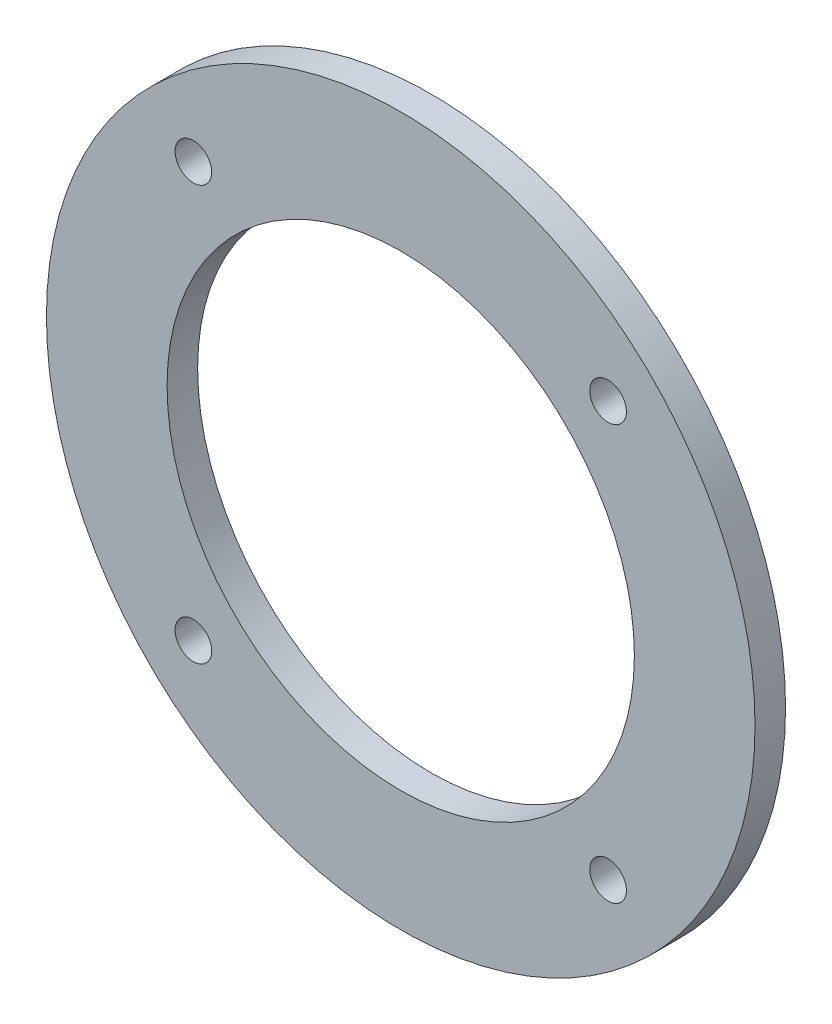
SolidWorks part; units mm, degrees
ref_plane "Front Plane" through (0, 0, 0) normal (0, 0, 1) x (1, 0, 0)
ref_plane "Top Plane" through (0, 0, 0) normal (0, 1, 0) x (1, 0, 0)
ref_plane "Right Plane" through (0, 0, 0) normal (1, 0, 0) x (0, 0, -1)
sketch "Esquisse1" plane through (0, 0, 0) normal (0, 0, 1) x (1, 0, 0)
  line L0 (0, 0) -> (61.2651, 61.2651) construction
  line L1 (0, 0) -> (108.3265, 0) construction
  circle A0 centre (0, 0) radius 38.25
  circle A1 centre (0, 0) radius 58
  circle A2 centre (0, 0) radius 48 construction
  circle A3 centre (33.9411, 33.9411) radius 3
  circle A4 centre (33.9411, -33.9411) radius 3
  circle A5 centre (-33.9411, -33.9411) radius 3
  circle A6 centre (-33.9411, 33.9411) radius 3
  point P8 (-26.8574, 21.5881)
  point P10 (0, 0)
  point P18 (0, 0)
  dimension "D1" = 76.5
  dimension "D2" = 6
  dimension "D3" = 96
  dimension "D4" = 10
  dimension "D5" = 45
  dimension "D6" = 4
extrude "Boss.-Extru.1" add sketch "Esquisse1" along normal blind 5
